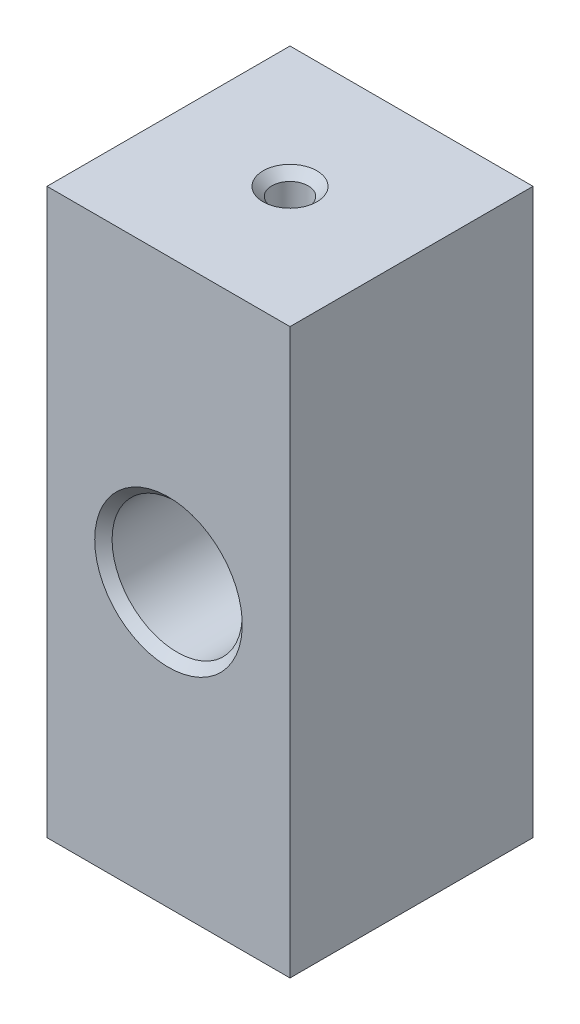
SolidWorks part; units mm, degrees
ref_plane "Piano frontale" through (0, 0, 0) normal (0, 0, 1) x (1, 0, 0)
ref_plane "Piano superiore" through (0, 0, 0) normal (0, 1, 0) x (1, 0, 0)
ref_plane "Piano destro" through (0, 0, 0) normal (1, 0, 0) x (0, 0, -1)
sketch "Sketch1" plane through (0, 0, 0) normal (0, 0, 1) x (1, 0, 0)
  line L1 (0, 0) -> (28, 0)
  line L2 (0, 0) -> (0, 65)
  line L3 (0, 65) -> (28, 65)
  line L4 (28, 0) -> (28, 65)
  circle A0 centre (14, 32.5) radius 7.5
  dimension "D5" = 15
  dimension "D1" = 28
  dimension "D2" = 65
  dimension "D3" = 32.5
  dimension "D4" = 14
extrude "Boss-Extrude1" add sketch "Sketch1" along normal blind 28
sketch "Sketch2" plane through (0, 0, 0) normal (0, -1, 0) x (1, 0, 0)
  line L0 (0, 28) -> (28, 28) construction
  line L1 (28, 28) -> (28, 0) construction
  line L2 (0, 0) -> (28, 0) construction
  line L3 (0, 28) -> (0, 0) construction
  line L4 (0, 28) -> (28, 28)
  line L5 (28, 28) -> (28, 0)
  line L6 (0, 0) -> (28, 0)
  line L7 (0, 28) -> (0, 0)
  circle A0 centre (14, 11) radius 2.5
  dimension "D3" = 5
  dimension "D1" = 11
  dimension "D2" = 14
hole_wizard "M5 Tapped Hole3" positions "Sketch4" profile "Sketch5" tap size "M5" standard "ISO"
sketch "Sketch4" plane through (0, 0, 0) normal (0, -1, 0) x (-1, 0, 0)
  point P0 (-14, -11)
sketch "Sketch5" plane through (14, 0, 11) normal (1, 0, 0) x (0, 0, -1)
  line L0 (0, 0) -> (0, 20)
  line L1 (0, 20) -> (2.1, 18.7382)
  line L2 (2.1, 18.7382) -> (2.1, 0)
  line L5 (2.1, 0) -> (0, 0)
  line L10 (0, 20) -> (-2.1, 18.7382) construction
  line L11 (0, -6.35) -> (0, 107.95) construction
  dimension "Tap Drill Dia." = 4.2
  dimension "Tap Drill Depth" = 20
  dimension "Drill Angle" = 118
cosmetic thread "Hole Thread1" parameters "D1"=16, "D2"=5
sketch "Sketch6" plane through (0, 65, 0) normal (0, 1, 0) x (1, 0, 0)
  line L0 (28, -28) -> (28, 0) construction
  line L1 (0, -28) -> (28, -28) construction
  line L2 (0, -28) -> (0, 0) construction
  line L3 (0, 0) -> (28, 0) construction
  line L4 (28, -28) -> (28, 0)
  line L5 (0, -28) -> (28, -28)
  line L6 (0, -28) -> (0, 0)
  line L7 (0, 0) -> (28, 0)
  circle A0 centre (14, -14) radius 2.5
  point P3 (14, -14)
  dimension "D1" = 5
  dimension "D2" = 14
  dimension "D3" = 14
hole_wizard "M5 Tapped Hole4" positions "Sketch6" profile "Sketch7" tap size "M5" standard "ISO"
sketch "Sketch7" plane through (14, 65, 14) normal (1, 0, 0) x (0, 0, 1)
  line L0 (0, 0) -> (0, 20)
  line L1 (0, 20) -> (2.1, 18.7382)
  line L2 (2.1, 18.7382) -> (2.1, 0)
  line L5 (2.1, 0) -> (0, 0)
  line L10 (0, 20) -> (-2.1, 18.7382) construction
  line L11 (0, -6.35) -> (0, 107.95) construction
  dimension "Tap Drill Dia." = 4.2
  dimension "Tap Drill Depth" = 20
  dimension "Drill Angle" = 118
cosmetic thread "Hole Thread2" parameters "D1"=16, "D2"=5
chamfer "Chamfer1" distance 1 angle 45 4 edges at (14, 0, 8.9) (14, 65, 16.1) (21.5, 32.5, 28) (21.5, 32.5, 0)
